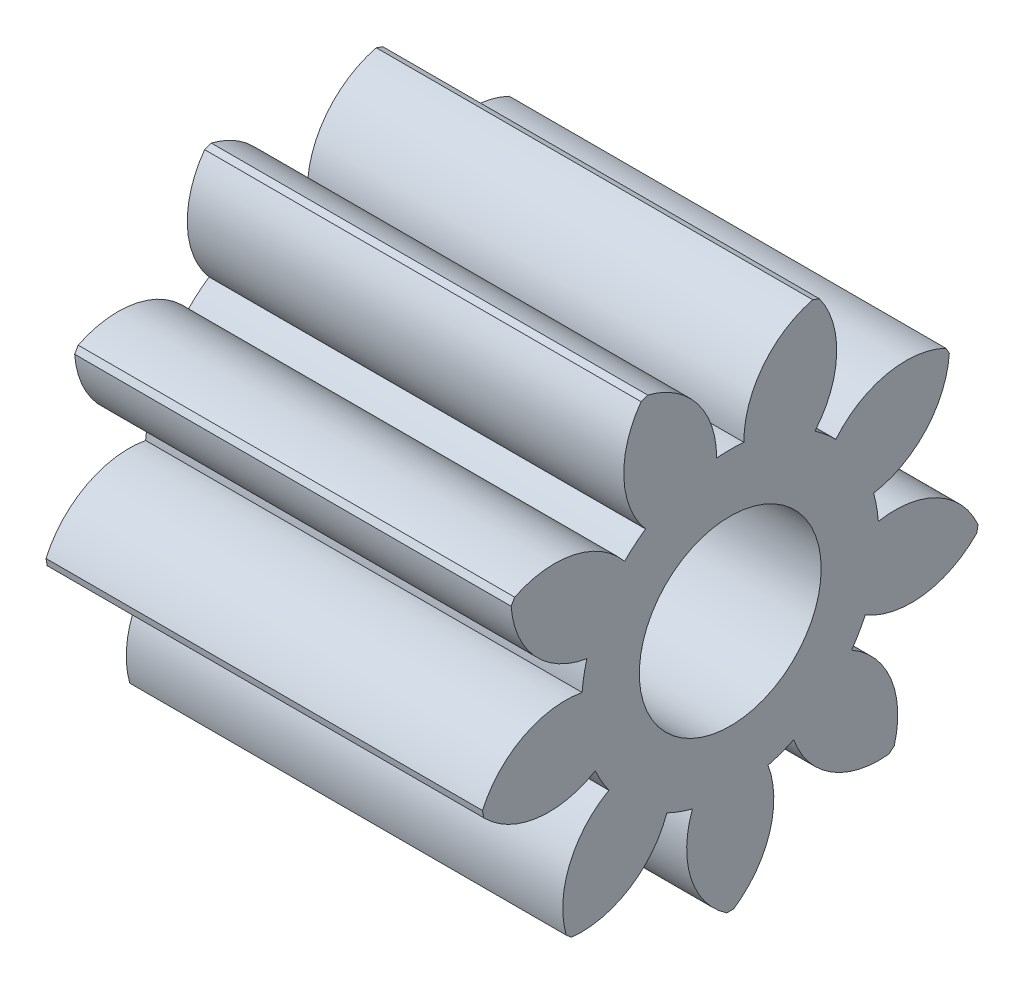
SolidWorks part; units mm, degrees
ref_plane "Plane1" through (0, 0, 0) normal (0, 0, 1) x (1, 0, 0)
ref_plane "Plane2" through (0, 0, 0) normal (0, 1, 0) x (1, 0, 0)
ref_plane "Plane3" through (0, 0, 0) normal (1, 0, 0) x (0, 0, -1)
sketch "BasProSke" plane through (0, 0, 0) normal (0, 1, 0) x (1, 0, 0)
  line L0 (-10, 0) -> (60, 0) construction
  line L1 (0, 0) -> (0, 6.9)
  line L2 (0, 0) -> (12, 0)
  line L3 (12, 0) -> (12, 6.9)
  line L4 (12, 6.9) -> (0, 6.9)
  dimension "Diameter" = 13.8
  dimension "Thickness" = 12
revolve "Base-Revolve" add sketch "BasProSke" angle 360 about L0
sketch "TooCutSke" plane through (0, 0, 0) normal (1, 0, 0) x (0, 0, -1)
  line L1 (0, 0) -> (0, 107) construction
  line L2 (0, 0) -> (-0.8687, 5.5828) construction
  line L3 (0, 0) -> (-3.4474, 10.61) construction
  line L4 (-0.8687, 5.5828) -> (-1.7237, 5.305) construction
  arc A0 (0.3749, 4.0693) -> (-0.3749, 4.0693) centre (0, 0) ccw
  arc A1 (2.3145, 6.5273) -> (-2.3145, 6.5273) centre (0, 0) ccw
  circle A2 centre (0, 0) radius 5.65 construction
  circle A3 centre (0, 0) radius 5 construction
  arc A4 (-0.3749, 4.0693) -> (-2.3145, 6.5273) centre (-2.8748, 4.0909) ccw
  arc A5 (2.3145, 6.5273) -> (0.3749, 4.0693) centre (2.8748, 4.0909) ccw
  dimension "Root_dia" = 8.173
  dimension "Overcut_dia" = 13.851
  dimension "Pitch_dia" = 11.3
  dimension "Base_dia" = 10
  dimension "Flank_rad" = 2.5
  dimension "Half_ang" = 18
  dimension "Half_CT" = 0.899
extrude "ToothCut" cut sketch "TooCutSke" along normal through all
pattern_circular "Круговой массив1" count 9 over 360 about axis through (0, 0, 0) along (1, 0, 0) of "ToothCut"
sketch "Эскиз1" plane through (12, 0, 0) normal (1, 0, 0) x (0, 0, -1)
  circle A0 centre (0, 0) radius 2.5
  dimension "D1" = 5
extrude "Вырез-Вытянуть1" cut sketch "Эскиз1" against normal through all
scale "Масштаб1" scale about centroid uniform scaling yes scale factor 1.03
equation "' \"Module@HoldingSke\" = 6.35"
equation "' \"Num_teeth@HoldingSke\" = 12"
equation "' \"Ap@HoldingSke\" =  20"
equation "' \"Width@HoldingSke\" = 0.5 * 25.4"
equation "' \"Hub_dia@HoldingSke\"= 1 * 25.4"
equation "' \"Overall_len@HoldingSke\" = 1.0 * 25.4"
equation "' \"Bore@HoldingSke\" = 0.75 * 25.4"
equation "' \"T_dim@HoldingSke\" = 0.1 * 25.4"
equation "' \"Width@KeySke\" = 0.25 * 25.4"
equation "' \"Show_teeth@HoldingSke\" = 13"
equation "' \"Backlash@HoldingSke\" = 0.009 * 25.4"
equation "' \"Addendum_fac@HoldingSke\" = 1.0"
equation "' \"Dedendum_fac@HoldingSke\" = 1.25"
equation "' \"Dedendum_add@HoldingSke\" = 0.00005 * 25.4"
equation "' \"Clearance_fac@HoldingSke\" = 0.25"
equation "\"Pitch@HoldingSke\" = 1 / \"Module@HoldingSke\""
equation "\"Half_ang@TooCutSke\" = 180 / \"Num_teeth@HoldingSke\""
equation "\"Half_CT@TooCutSke\" = \"Num_teeth@HoldingSke\" / \"Pitch@HoldingSke\" * sin((3.14159265 / 2 / \"Num_teeth@HoldingSke\")) / 2 - 7 * \"Backlash@HoldingSke\" / 4"
equation "\"Flank_rad@TooCutSke\" = \"Num_teeth@HoldingSke\" / \"Pitch@HoldingSke\" / 5"
equation "\"Radius@RootFillets\" = \"Clearance_fac@HoldingSke\" / \"Pitch@HoldingSke\" + \"Dedendum_add@HoldingSke\""
equation "\"Break_rad@Breaks\" = 0.02 / \"Pitch@HoldingSke\""
equation "\"Thickness@HoldingSke\" = \"Width@HoldingSke\""
equation "\"OAL@HoldingSke\" = \"Thickness@HoldingSke\""
equation "\"MHD@HoldingSke\" = (\"Num_teeth@HoldingSke\" + 2) / \"Pitch@HoldingSke\" - 2 * (\"Addendum_fac@HoldingSke\" + \"Dedendum_fac@HoldingSke\")  / \"Pitch@HoldingSke\" - \"Dedendum_add@HoldingSke\" * 2"
equation "\"MBD@HoldingSke\" = (\"Num_teeth@HoldingSke\" + 2) / \"Pitch@HoldingSke\" - 2 * (\"Addendum_fac@HoldingSke\" + \"Dedendum_fac@HoldingSke\")  / \"Pitch@HoldingSke\" - \"Dedendum_add@HoldingSke\" * 2 - 0.002 * 25.4"
equation "\"MHD@HoldingSke\" = ((sgn( \"MHD@HoldingSke\" - \"Hub_dia@HoldingSke\" )-1)*( \"MHD@HoldingSke\" - \"Hub_dia@HoldingSke\" ))/-2+ \"Hub_dia@HoldingSke\""
equation "\"MBD@HoldingSke\" = ((sgn( \"MBD@HoldingSke\" - \"Bore@HoldingSke\" )-1)*( \"MBD@HoldingSke\" - \"Bore@HoldingSke\" ))/-2+ \"Bore@HoldingSke\""
equation "\"OAL@HoldingSke\" = ((sgn( \"OAL@HoldingSke\" - \"Overall_len@HoldingSke\" )+1)*( \"OAL@HoldingSke\" - \"Overall_len@HoldingSke\" ))/2 + \"Overall_len@HoldingSke\" + 0.000002 * 25.4"
equation "\"Num_teeth@TeethCuts\" = int( \"Show_teeth@HoldingSke\" ) + 1"
equation "\"Num_teeth@TeethCuts\" = ((sgn( \"Num_teeth@TeethCuts\" - \"Num_teeth@HoldingSke\" )-1)*( \"Num_teeth@TeethCuts\" - \"Num_teeth@HoldingSke\" ))/-2+ \"Num_teeth@HoldingSke\""
equation "\"Num_teeth@TeethCuts\" = ((sgn( \"Num_teeth@TeethCuts\" - 2.0)+1)*( \"Num_teeth@TeethCuts\" - 2.0))/2 +2.0"
equation "\"Angle@TeethCuts\" = 360.0 / \"Num_teeth@HoldingSke\""
equation "' \"Fillet_rad@BasProSke\" =  \"Thickness@HoldingSke\" * 0.05"
equation "\"MHD@HoldingSke\" = ((sgn( \"MHD@HoldingSke\" - \"Root_dia@TooCutSke\" )-1)*( \"MHD@HoldingSke\" - \"Root_dia@TooCutSke\" ))/-2+ \"Root_dia@TooCutSke\""
equation "\"Diameter@HubNeaOneSke\" = \"MHD@HoldingSke\""
equation "\"Length@HubNearOne\" = \"OAL@HoldingSke\" - \"Thickness@BasProSke\""
equation "\"Diameter@HubNeaBotSke\" = \"MHD@HoldingSke\""
equation "\"Length@HubNearBoth\" = ( \"OAL@HoldingSke\" - \"Thickness@BasProSke\" ) / 2.0"
equation "\"Thickness@FarPln\" = \"Thickness@BasProSke\""
equation "\"Diameter@HubFarSke\" = \"MHD@HoldingSke\""
equation "\"Length@HubFar\" = ( \"OAL@HoldingSke\" - \"Thickness@BasProSke\" ) / 2.0"
equation "\"Diameter@BorSke\" = \"MBD@HoldingSke\""
equation "\"D1@Bore\" = \"OAL@HoldingSke\" * 2.0"
equation "\"D1@Keyway\" = \"OAL@HoldingSke\" * 2.0"
equation "\"Offset@KeySke\" = \"T_dim@HoldingSke\" + \"MBD@HoldingSke\" / 2.0"
